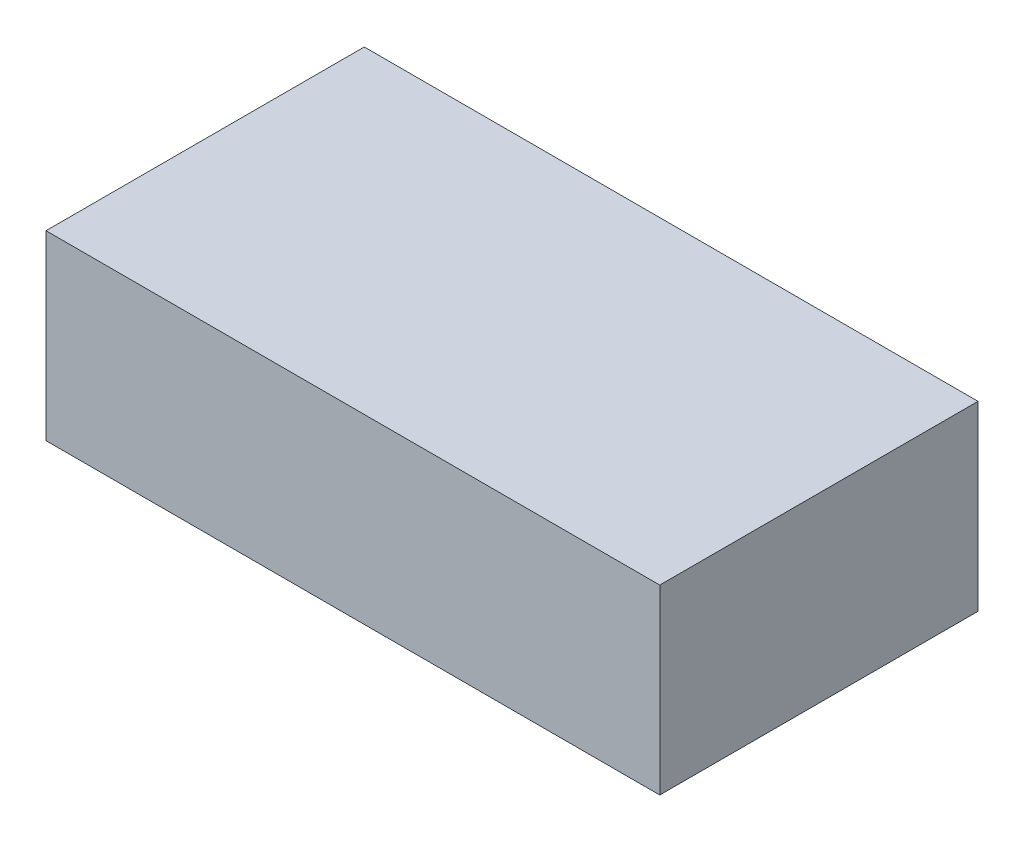
SolidWorks part; units mm, degrees
ref_plane "前视基准面" through (0, 0, 0) normal (0, 0, 1) x (1, 0, 0)
ref_plane "上视基准面" through (0, 0, 0) normal (0, 1, 0) x (1, 0, 0)
ref_plane "右视基准面" through (0, 0, 0) normal (1, 0, 0) x (0, 0, -1)
sketch "草图1" plane through (0, 0, 0) normal (0, 1, 0) x (1, 0, 0)
  line L1 (0, 0) -> (162, 0)
  line L2 (0, 0) -> (0, 84)
  line L3 (0, 84) -> (162, 84)
  line L4 (162, 0) -> (162, 84)
  dimension "D1" = 162
  dimension "D2" = 84
extrude "凸台-拉伸1" add sketch "草图1" along normal blind 48
